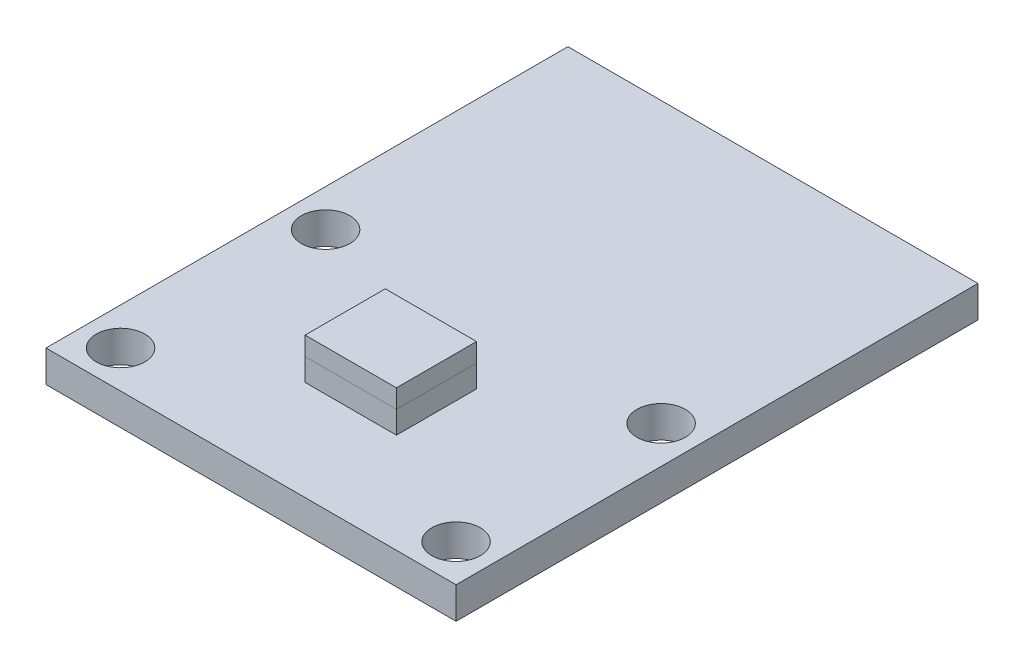
SolidWorks part; units mm, degrees
ref_plane "Front" through (0, 0, 0) normal (0, 0, 1) x (1, 0, 0)
ref_plane "Top" through (0, 0, 0) normal (0, 1, 0) x (1, 0, 0)
ref_plane "Right" through (0, 0, 0) normal (1, 0, 0) x (0, 0, -1)
sketch "Sketch1" plane through (0, 0, 0) normal (0, 1, 0) x (1, 0, 0)
  line L0 (-9, -5.5) -> (9, 5.5) construction
  line L1 (-11, 20.5) -> (11, 20.5)
  line L2 (-11, 20.5) -> (-11, -7.5)
  line L3 (-11, -7.5) -> (11, -7.5)
  line L4 (11, 20.5) -> (11, -7.5)
  line L5 (-9, -5.5) -> (-11, -7.5) construction
  circle A0 centre (-9, -5.5) radius 1.3
  circle A1 centre (9, -5.5) radius 1.3
  circle A2 centre (9, 5.5) radius 1.3
  circle A3 centre (-9, 5.5) radius 1.3
  point P5 (0, 20.5)
  point P9 (0, 0)
  point P10 (11, -8.4107)
  point P16 (0, 0)
  point P17 (0, 0)
  dimension "D5" = 2.6
  dimension "D1" = 28
  dimension "D2" = 22
  dimension "D6" = 11
  dimension "D7" = 45
  dimension "D8" = 18
  dimension "D3" = 2
  dimension "D4" = 2
extrude "Boss-Extrude1" add sketch "Sketch1" along normal blind 1.7
sketch "Sketch2" plane through (0, 1.7, 0) normal (0, 1, 0) x (1, 0, 0)
  line L1 (-2.45, -2.15) -> (2.45, -2.15)
  line L2 (-2.45, -2.15) -> (-2.45, 2.15)
  line L3 (-2.45, 2.15) -> (2.45, 2.15)
  line L4 (2.45, -2.15) -> (2.45, 2.15)
  line L5 (-2.45, -2.15) -> (2.45, 2.15) construction
  line L6 (-2.45, 2.15) -> (2.45, -2.15) construction
  point P0 (0, 0)
  dimension "D1" = 4.9
  dimension "D2" = 4.3
extrude "Boss-Extrude2" add sketch "Sketch2" along normal blind 1.2
sketch "Sketch3" plane through (0, 2.9, 0) normal (0, 1, 0) x (1, 0, 0)
  line L4 (2.45, -2.15) -> (2.45, 2.15)
  line L5 (2.45, 2.15) -> (-2.45, 2.15)
  line L6 (-2.45, 2.15) -> (-2.45, -2.15)
  line L7 (-2.45, -2.15) -> (2.45, -2.15)
  line L8 (2.45, -2.15) -> (2.45, 2.15)
  line L9 (2.45, 2.15) -> (-2.45, 2.15)
  line L10 (-2.45, 2.15) -> (-2.45, -2.15)
  line L11 (-2.45, -2.15) -> (2.45, -2.15)
  dimension "D1" = 0
extrude "Boss-Extrude3" add sketch "Sketch3" along normal blind 1 separate body
